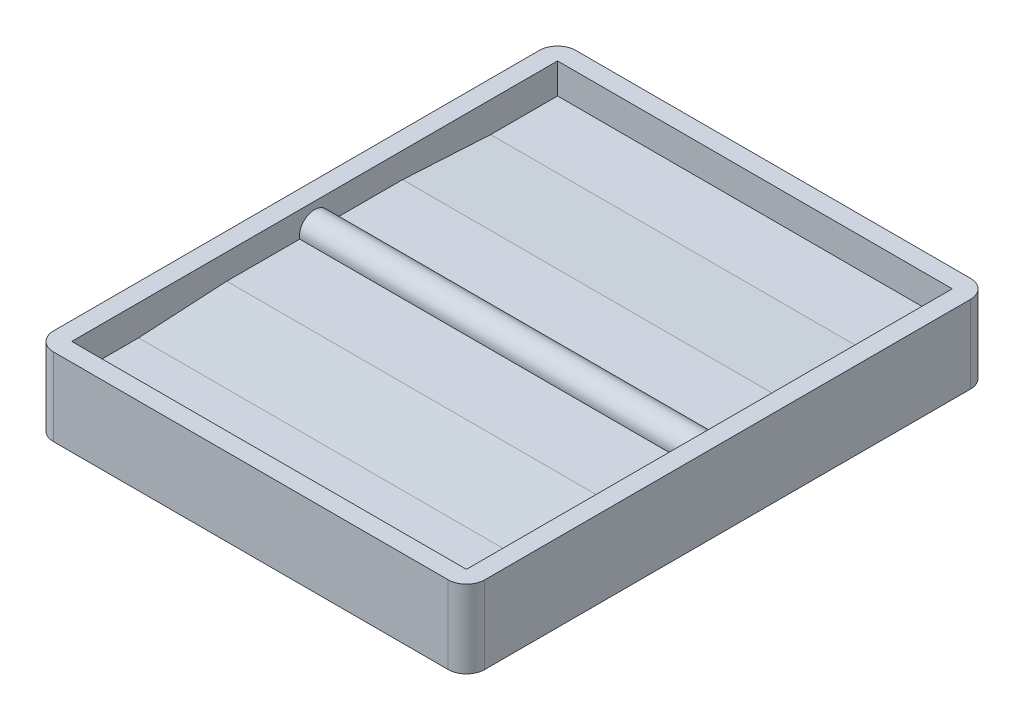
SolidWorks part; units mm, degrees
ref_plane "Front Plane" through (0, 0, 0) normal (0, 0, 1) x (1, 0, 0)
ref_plane "Top Plane" through (0, 0, 0) normal (0, 1, 0) x (1, 0, 0)
ref_plane "Right Plane" through (0, 0, 0) normal (1, 0, 0) x (0, 0, -1)
sketch "Sketch1" plane through (0, 0, 0) normal (0, 1, 0) x (1, 0, 0)
  line L1 (-32.5, -43) -> (32.5, -43)
  line L2 (-35.5, -40) -> (-35.5, 40)
  line L3 (-32.5, 43) -> (32.5, 43)
  line L4 (35.5, -40) -> (35.5, 40)
  line L5 (-35.5, -43) -> (35.5, 43) construction
  line L6 (-35.5, 43) -> (35.5, -43) construction
  arc A0 (-32.5, -43) -> (-35.5, -40) centre (-32.5, -40) cw
  arc A1 (-35.5, 40) -> (-32.5, 43) centre (-32.5, 40) cw
  arc A2 (35.5, 40) -> (32.5, 43) centre (32.5, 40) ccw
  arc A3 (32.5, -43) -> (35.5, -40) centre (32.5, -40) ccw
  point P0 (0, 0)
  dimension "D1" = 3
extrude "Boss-Extrude1" add sketch "Sketch1" along normal blind 12.8
sketch "Sketch2" plane through (0, 12.8, 0) normal (0, 1, 0) x (1, 0, 0)
  line L0 (-35.5, 40) -> (-35.5, -40) construction
  line L1 (-32.5, -40) -> (32.5, -40)
  line L2 (-32.5, -40) -> (-32.5, 40)
  line L3 (-32.5, 40) -> (32.5, 40)
  line L4 (32.5, -40) -> (32.5, 40)
  line L5 (-32.5, -40) -> (32.5, 40) construction
  line L6 (-32.5, 40) -> (32.5, -40) construction
  line L7 (-32.5, -43) -> (32.5, -43) construction
  point P0 (0, 0)
  dimension "D1" = 3
  dimension "D2" = 3
extrude "Cut-Extrude1" cut sketch "Sketch2" against normal blind 5
sketch "Sketch3" plane through (-32.5, 0, 0) normal (1, 0, 0) x (0, 0, -1)
  circle A0 centre (0, 9.0966) radius 2.5
  point P2 (0, 9.3144)
  point P3 (0, 0)
  point P4 (0, 9.0966)
extrude "Boss-Extrude2" add sketch "Sketch3" along normal up to surface (65 mm away) up to face at (32.5, 10.3, 0)
sketch "Sketch4" plane through (32.5, 0, 0) normal (-1, 0, 0) x (0, 0, 1)
  line L0 (0, 0) -> (0, 27.2854) construction
  line L1 (-2.4548, 8.6234) -> (-14.4811, 8.6234)
  line L2 (-14.4811, 8.6234) -> (-28.9918, 7.8)
  line L3 (2.4524, 8.6112) -> (14.4811, 8.6234)
  line L4 (14.4811, 8.6234) -> (28.9918, 7.8)
  line L5 (2.1375, 7.8) -> (40, 7.8)
  line L6 (40, 7.8) -> (40, 12.8)
  line L7 (40, 12.8) -> (-40, 12.8)
  line L8 (-40, 12.8) -> (-40, 7.8)
  line L9 (-40, 7.8) -> (-2.1375, 7.8)
  line L10 (2.1375, 7.8) -> (28.9918, 7.8)
  line L14 (-28.9918, 7.8) -> (-2.1375, 7.8)
  arc A0 (-2.4548, 8.6234) -> (-2.1375, 7.8) centre (0, 9.0966) ccw
  arc A1 (2.1375, 7.8) -> (-2.1375, 7.8) centre (0, 9.0966) ccw
  arc A2 (2.1375, 7.8) -> (2.4524, 8.6112) centre (0, 9.0966) ccw
  point P13 (-2.5, 9.0966)
  point P16 (0, 0)
  point P17 (-2.5, 9.0966)
  point P18 (0, 0)
  point P19 (0, 0)
  point P20 (-2.5, 9.0966)
  point P21 (0, 0)
  point P22 (2.4524, 8.6137)
  point P23 (-14.4811, 8.6234)
  dimension "D1" = 0
extrude "Boss-Extrude3" add sketch "Sketch4" along normal up to surface (65 mm away) up to face at (-32.5, 10.0994, 0)
